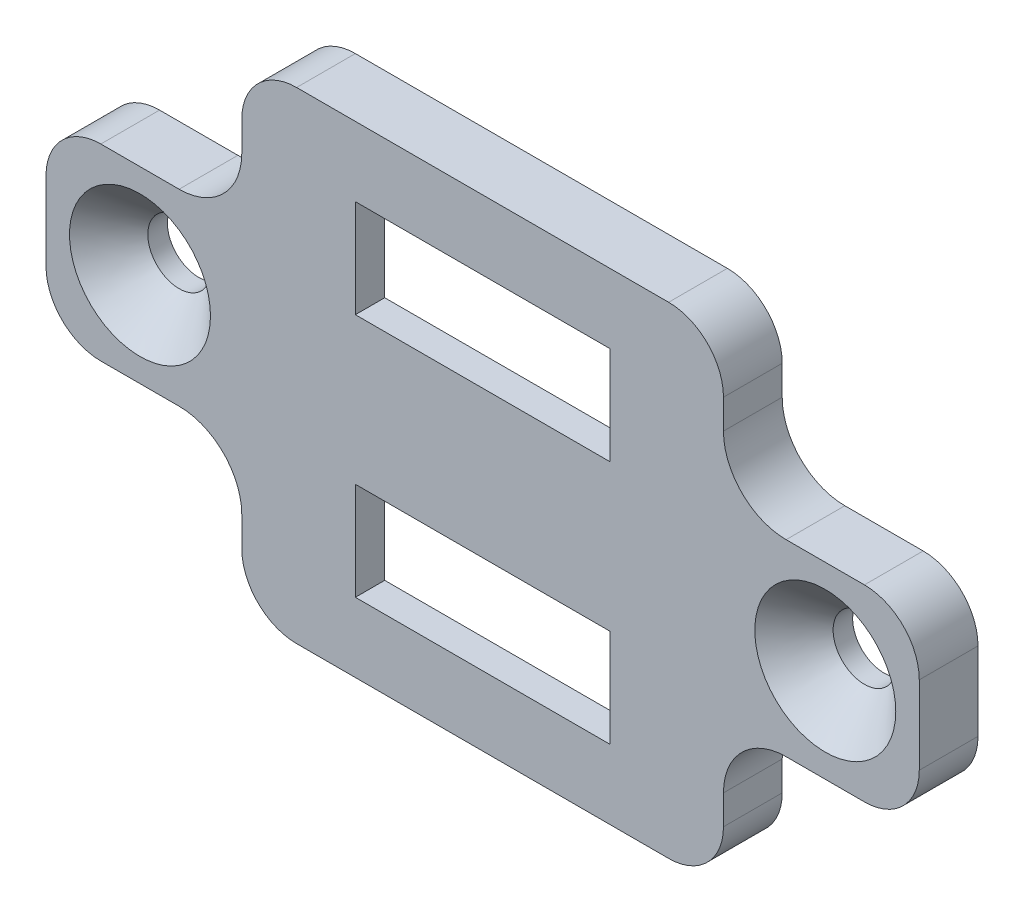
SolidWorks part; units mm, degrees
ref_plane "Plan de face" through (0, 0, 0) normal (0, 0, 1) x (1, 0, 0)
ref_plane "Plan de dessus" through (0, 0, 0) normal (0, 1, 0) x (1, 0, 0)
ref_plane "Plan de droite" through (0, 0, 0) normal (1, 0, 0) x (0, 0, -1)
sketch "Esquisse1" plane through (0, 0, 0) normal (0, 0, 1) x (1, 0, 0)
  line L0 (0, -1000) -> (0, 49000) construction
  line L1 (-9.5, 12.5) -> (9.5, 12.5) construction
  line L2 (-12.5, 9.5) -> (-12.5, 8) construction
  line L3 (-9.5, -12.5) -> (9.5, -12.5) construction
  line L4 (12.5, 9.5) -> (12.5, 8) construction
  line L5 (-12.5, 12.5) -> (12.5, -12.5) construction
  line L6 (-12.5, -12.5) -> (12.5, 12.5) construction
  line L7 (-19.5, 5) -> (-15.5, 5) construction
  line L8 (-22.5, 2) -> (-22.5, -2) construction
  line L9 (-19.5, -5) -> (-15.5, -5) construction
  line L11 (-22.5, 5) -> (-12.5, -5) construction
  line L12 (-22.5, -5) -> (-12.5, 5) construction
  line L13 (22.5, -5) -> (12.5, 5) construction
  line L14 (22.5, 5) -> (12.5, -5) construction
  line L16 (19.5, -5) -> (15.5, -5) construction
  line L17 (22.5, 2) -> (22.5, -2) construction
  line L18 (19.5, 5) -> (15.5, 5) construction
  line L19 (-12.5, -8) -> (-12.5, -9.5) construction
  line L20 (12.5, -8) -> (12.5, -9.5) construction
  line L21 (-9.5, 12.3) -> (9.5, 12.3)
  line L22 (12.3, 9.5) -> (12.3, 8)
  line L23 (19.5, 4.8) -> (15.5, 4.8)
  line L24 (22.3, 2) -> (22.3, -2)
  line L25 (19.5, -4.8) -> (15.5, -4.8)
  line L26 (12.3, -8) -> (12.3, -9.5)
  line L27 (-9.5, -12.3) -> (9.5, -12.3)
  line L28 (-12.3, -8) -> (-12.3, -9.5)
  line L29 (-19.5, -4.8) -> (-15.5, -4.8)
  line L30 (-22.3, 2) -> (-22.3, -2)
  line L31 (-19.5, 4.8) -> (-15.5, 4.8)
  line L32 (-12.3, 9.5) -> (-12.3, 8)
  arc A0 (-15.5, 5) -> (-12.5, 8) centre (-15.5, 8) ccw construction
  arc A1 (-9.5, 12.5) -> (-12.5, 9.5) centre (-9.5, 9.5) ccw construction
  arc A2 (9.5, 12.5) -> (12.5, 9.5) centre (9.5, 9.5) cw construction
  arc A3 (15.5, 5) -> (12.5, 8) centre (15.5, 8) cw construction
  arc A4 (19.5, 5) -> (22.5, 2) centre (19.5, 2) cw construction
  arc A5 (22.5, -2) -> (19.5, -5) centre (19.5, -2) cw construction
  arc A6 (15.5, -5) -> (12.5, -8) centre (15.5, -8) ccw construction
  arc A7 (9.5, -12.5) -> (12.5, -9.5) centre (9.5, -9.5) ccw construction
  arc A8 (-12.5, -9.5) -> (-9.5, -12.5) centre (-9.5, -9.5) ccw construction
  arc A9 (-15.5, -5) -> (-12.5, -8) centre (-15.5, -8) cw construction
  arc A10 (-22.5, -2) -> (-19.5, -5) centre (-19.5, -2) ccw construction
  arc A11 (-19.5, 5) -> (-22.5, 2) centre (-19.5, 2) ccw construction
  arc A12 (9.5, 12.3) -> (12.3, 9.5) centre (9.5, 9.5) cw
  arc A13 (15.5, 4.8) -> (12.3, 8) centre (15.5, 8) cw
  arc A14 (19.5, 4.8) -> (22.3, 2) centre (19.5, 2) cw
  arc A15 (22.3, -2) -> (19.5, -4.8) centre (19.5, -2) cw
  arc A16 (15.5, -4.8) -> (12.3, -8) centre (15.5, -8) ccw
  arc A17 (9.5, -12.3) -> (12.3, -9.5) centre (9.5, -9.5) ccw
  arc A18 (-12.3, -9.5) -> (-9.5, -12.3) centre (-9.5, -9.5) ccw
  arc A19 (-15.5, -4.8) -> (-12.3, -8) centre (-15.5, -8) cw
  arc A20 (-22.3, -2) -> (-19.5, -4.8) centre (-19.5, -2) ccw
  arc A21 (-19.5, 4.8) -> (-22.3, 2) centre (-19.5, 2) ccw
  arc A22 (-15.5, 4.8) -> (-12.3, 8) centre (-15.5, 8) ccw
  arc A23 (-9.5, 12.3) -> (-12.3, 9.5) centre (-9.5, 9.5) ccw
  circle A24 centre (-17.5, 0) radius 1.6
  circle A25 centre (17.5, 0) radius 1.6
  point P0 (0, 0)
  point P7 (-17.5, 0)
  point P17 (17.5, 0)
  dimension "D3" = 3
  dimension "D5" = 3.2
  dimension "D1" = 25
  dimension "D2" = 10
  dimension "D4" = 0.2
extrude "Boss.-Extru.1" add sketch "Esquisse1" along normal blind 3
sketch "Esquisse2" plane through (0, 0, 0) normal (0, 0, -1) x (-1, 0, 0)
  line L1 (-8.75, 11.75) -> (8.75, 11.75)
  line L2 (-11.75, 8.75) -> (-11.75, -8.75)
  line L3 (-8.75, -11.75) -> (8.75, -11.75)
  line L4 (11.75, 8.75) -> (11.75, -8.75)
  line L5 (-11.75, 11.75) -> (11.75, -11.75) construction
  line L6 (-11.75, -11.75) -> (11.75, 11.75) construction
  arc A0 (-11.75, -8.75) -> (-8.75, -11.75) centre (-8.75, -8.75) ccw
  arc A1 (8.75, -11.75) -> (11.75, -8.75) centre (8.75, -8.75) ccw
  arc A2 (8.75, 11.75) -> (11.75, 8.75) centre (8.75, 8.75) cw
  arc A3 (-8.75, 11.75) -> (-11.75, 8.75) centre (-8.75, 8.75) ccw
  point P0 (0, 0)
  dimension "D1" = 3
  dimension "24" = 23.5
extrude "Enlèv. mat.-Extru.1" cut sketch "Esquisse2" against normal blind 1.5
sketch "Esquisse4" plane through (0, 0, 1.5) normal (0, 0, -1) x (-1, 0, 0)
  line L0 (8.75, 11.75) -> (-8.75, 11.75) construction
  line L1 (-6.5, 8.75) -> (6.5, 8.75)
  line L2 (-6.5, 8.75) -> (-6.5, 3.75)
  line L3 (-6.5, 3.75) -> (6.5, 3.75)
  line L4 (6.5, 8.75) -> (6.5, 3.75)
  line L5 (-6.5, 8.75) -> (6.5, 3.75) construction
  line L6 (-6.5, 3.75) -> (6.5, 8.75) construction
  line L7 (-1000, 0) -> (49000, 0) construction
  line L8 (-6.5, -3.75) -> (6.5, -3.75)
  line L9 (6.5, -8.75) -> (6.5, -3.75)
  line L10 (-6.5, -8.75) -> (6.5, -8.75)
  line L11 (-6.5, -8.75) -> (-6.5, -3.75)
  point P0 (0, 6.25)
  dimension "D1" = 13
  dimension "D2" = 5
  dimension "D3" = 5.5
extrude "Enlèv. mat.-Extru.2" cut sketch "Esquisse4" against normal through all
chamfer "Chanfrein1" distance 2 angle 45 2 edges at (19.1, 0, 3) (-15.9, 0, 3)
